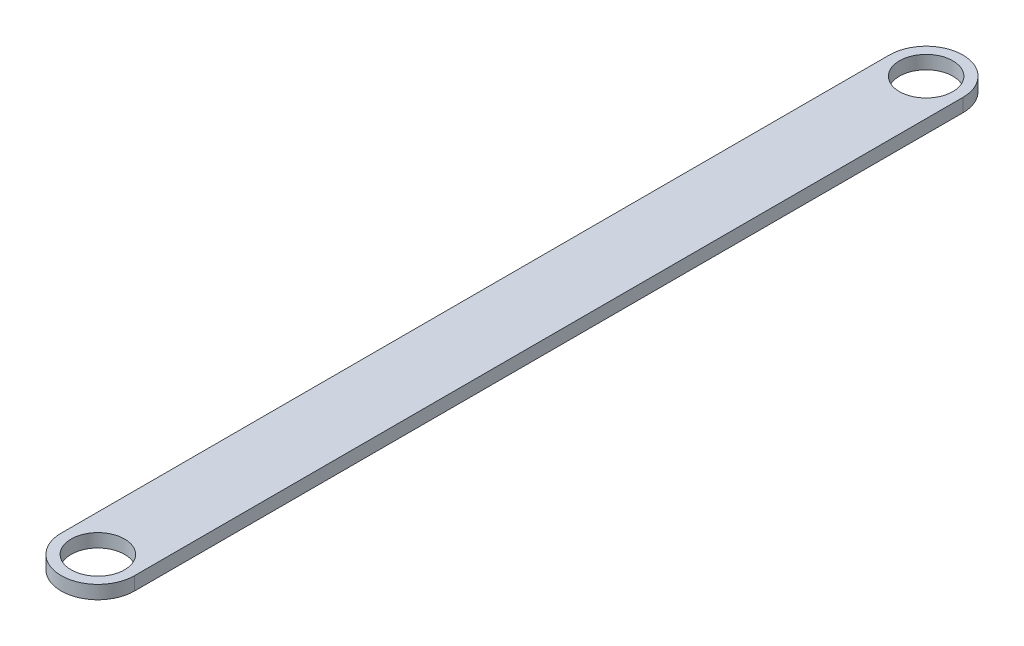
SolidWorks part; units mm, degrees
ref_plane "Front Plane" through (0, 0, 0) normal (0, 0, 1) x (1, 0, 0)
ref_plane "Top Plane" through (0, 0, 0) normal (0, 1, 0) x (1, 0, 0)
ref_plane "Right Plane" through (0, 0, 0) normal (1, 0, 0) x (0, 0, -1)
sketch "Sketch1" plane through (0, 0, 0) normal (0, 1, 0) x (1, 0, 0)
  line L0 (0, 0) -> (0, 124) construction
  line L1 (-5.5, 0) -> (-5.5, 124)
  line L2 (5.5, 0) -> (5.5, 124)
  arc A0 (-5.5, 0) -> (5.5, 0) centre (0, 0) ccw
  arc A1 (5.5, 124) -> (-5.5, 124) centre (0, 124) ccw
  circle A2 centre (0, 124) radius 4
  circle A3 centre (0, 0) radius 4
  point P3 (0, 62)
  dimension "D3" = 8
  dimension "D4" = 8
  dimension "D1" = 11
  dimension "D2" = 124
extrude "Boss-Extrude1" add sketch "Sketch1" along normal blind 2
